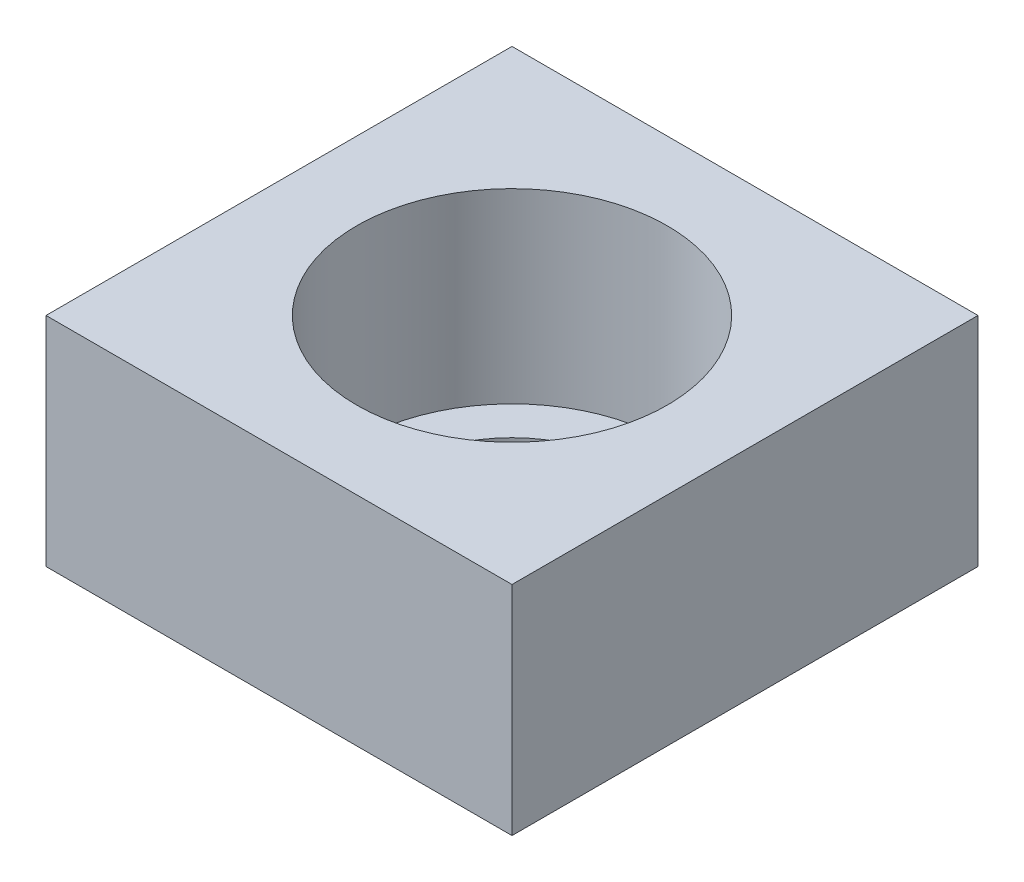
SolidWorks part; units mm, degrees
material "6061 Alloy"
ref_plane "Front Plane" through (0, 0, 0) normal (0, 0, 1) x (1, 0, 0)
ref_plane "Top Plane" through (0, 0, 0) normal (0, 1, 0) x (1, 0, 0)
ref_plane "Right Plane" through (0, 0, 0) normal (1, 0, 0) x (0, 0, -1)
sketch "Sketch2" plane through (0, 0, 0) normal (0, 1, 0) x (1, 0, 0)
  line L1 (-22.5, 22.5) -> (22.5, 22.5)
  line L2 (-22.5, 22.5) -> (-22.5, -22.5)
  line L3 (-22.5, -22.5) -> (22.5, -22.5)
  line L4 (22.5, 22.5) -> (22.5, -22.5)
  line L5 (-22.5, 22.5) -> (22.5, -22.5) construction
  line L6 (-22.5, -22.5) -> (22.5, 22.5) construction
  circle A0 centre (0, 0) radius 11
  point P0 (0, 0)
  dimension "D3" = 22
  dimension "D1" = 45
  dimension "D2" = 45
extrude "Boss-Extrude1" add sketch "Sketch2" along normal blind 21
sketch "Sketch3" plane through (0, 21, 0) normal (0, 1, 0) x (1, 0, 0)
  circle A0 centre (0, 0) radius 15
  dimension "D1" = 30
extrude "Cut-Extrude1" cut sketch "Sketch3" against normal blind 18
